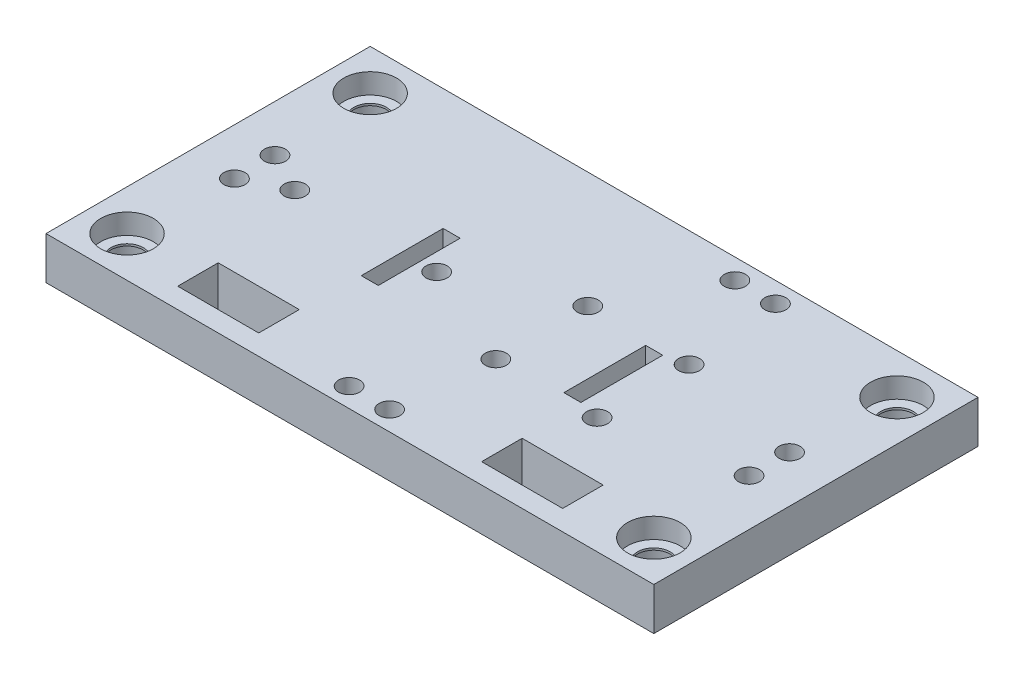
SolidWorks part; units mm, degrees
ref_plane "Front Plane" through (0, 0, 0) normal (0, 0, 1) x (1, 0, 0)
ref_plane "Top Plane" through (0, 0, 0) normal (0, 1, 0) x (1, 0, 0)
ref_plane "Right Plane" through (0, 0, 0) normal (1, 0, 0) x (0, 0, -1)
sketch "Sketch1" plane through (0, 0, 0) normal (0, 1, 0) x (1, 0, 0)
  line L1 (0, 0) -> (150, 0)
  line L2 (0, 0) -> (0, 80)
  line L3 (0, 80) -> (150, 80)
  line L4 (150, 0) -> (150, 80)
  dimension "D1" = 80
  dimension "D2" = 150
extrude "Boss-Extrude1" add sketch "Sketch1" along normal blind 10.5
sketch "Sketch10" plane through (0, 10.5, 0) normal (0, 1, 0) x (1, 0, 0)
  line L0 (75, 80) -> (75, 0) construction
  line L1 (0, 40) -> (150, 40) construction
  line L4 (0, 80) -> (0, 0)
  line L5 (0, 80) -> (0, 0) construction
  line L6 (0, 0) -> (150, 0)
  line L7 (0, 0) -> (150, 0) construction
  line L8 (150, 0) -> (150, 80)
  line L9 (150, 0) -> (150, 80) construction
  line L10 (150, 80) -> (0, 80)
  line L11 (150, 80) -> (0, 80) construction
  circle A0 centre (10, 10) radius 6.5
  circle A1 centre (140, 10) radius 6.5
  circle A3 centre (10, 70) radius 6.5
  circle A4 centre (140, 70) radius 6.5
  circle A5 centre (10, 10) radius 7.5
  circle A6 centre (10, 70) radius 7.5
  circle A7 centre (140, 70) radius 7.5
  circle A8 centre (140, 10) radius 7.5
  dimension "D4" = 13
  dimension "D2" = 10
  dimension "D3" = 10
  dimension "D1" = 0
  dimension "D5" = 1
extrude "Cut-Extrude8" cut sketch "Sketch10" against normal blind 5 contours A0 | A3 | A4 | A1 | L5 L7 L9 L11
ref_plane "MirrorPlane1" through (0, 5.25, 0) normal (0, 1, 0) x (1, 0, 0)
ref_plane "MirrorPlane2" through (0, 0, -40) normal (0, 0, 1) x (1, 0, 0)
ref_plane "MirrorPlane3" through (75, 0, 0) normal (-1, 0, 0) x (0, 0, 1)
mirror "Mirror1" about plane through (0, 5.25, 0) normal (0, 1, 0) of "Cut-Extrude8"
sketch "Sketch3" plane through (0, 10.5, 0) normal (0, 1, 0) x (1, 0, 0)
  line L0 (75, 80) -> (75, 0) construction
  line L5 (150, 80) -> (0, 80) construction
  line L6 (75, 5.775) -> (75, -5.775) construction
  line L7 (0, 0) -> (150, 0) construction
  line L8 (27.5, 15) -> (47.5, 15)
  line L9 (27.5, 15) -> (27.5, 5)
  line L10 (27.5, 5) -> (47.5, 5)
  line L11 (47.5, 15) -> (47.5, 5)
  line L12 (27.5, 15) -> (47.5, 5) construction
  line L13 (27.5, 5) -> (47.5, 15) construction
  line L15 (75, 80) -> (0, 0) construction
  line L16 (122.5, 5) -> (102.5, 5)
  line L17 (102.5, 15) -> (102.5, 5)
  line L18 (122.5, 15) -> (102.5, 15)
  line L19 (122.5, 15) -> (122.5, 5)
  point P0 (37.5, 10)
  point P16 (37.5, 40)
  dimension "D1" = 10
  dimension "D2" = 10
  dimension "D3" = 20
extrude "WireHoles" cut sketch "Sketch3" against normal up to next
sketch "Sketch6" plane through (0, 10.5, 0) normal (0, 1, 0) x (1, 0, 0)
  line L0 (75, 80) -> (75, 0) construction
  line L1 (150, 80) -> (0, 80) construction
  line L2 (0, 0) -> (150, 0) construction
  line L3 (38.9, 40) -> (21.4, 40) construction
  line L4 (73, 28.4) -> (4.8, 28.4) construction
  line L5 (73, 28.4) -> (73, 51.6) construction
  line L6 (73, 51.6) -> (4.8, 51.6) construction
  line L7 (4.8, 28.4) -> (4.8, 51.6) construction
  line L8 (73, 28.4) -> (4.8, 51.6) construction
  line L9 (73, 51.6) -> (4.8, 28.4) construction
  line L10 (38.9, 51.6) -> (38.9, 28.4) construction
  circle A0 centre (21.4, 40) radius 2.6
  circle A1 centre (56.4, 40) radius 2.6
  point P8 (38.9, 40)
  point P18 (75, 40)
  dimension "D5" = 5.2
  dimension "D1" = 68.2
  dimension "D2" = 23.2
  dimension "D3" = 2
  dimension "D4" = 17.5
extrude "4AACut" cut sketch "Sketch6" against normal blind 5.2
sketch "Sketch7" plane through (0, 10.5, 0) normal (0, 1, 0) x (1, 0, 0)
  line L0 (94.85, 51.35) -> (82.35, 51.35) construction
  line L1 (77, 42) -> (112.7, 42) construction
  line L2 (77, 42) -> (77, 60.7) construction
  line L3 (77, 60.7) -> (112.7, 60.7) construction
  line L4 (112.7, 42) -> (112.7, 60.7) construction
  line L5 (77, 42) -> (112.7, 60.7) construction
  line L6 (77, 60.7) -> (112.7, 42) construction
  line L7 (94.85, 60.7) -> (94.85, 42) construction
  line L8 (75, 80) -> (75, 0) construction
  line L9 (150, 80) -> (0, 80) construction
  line L10 (0, 0) -> (150, 0) construction
  line L11 (0, 40) -> (150, 40) construction
  line L12 (0, 80) -> (0, 0) construction
  line L13 (150, 0) -> (150, 80) construction
  circle A0 centre (82.35, 51.35) radius 2.6
  circle A1 centre (56.4, 40) radius 2.6 construction
  circle A2 centre (107.35, 51.35) radius 2.6
  circle A3 centre (82.35, 28.65) radius 2.6
  circle A4 centre (107.35, 28.65) radius 2.6
  point P0 (94.85, 51.35)
  dimension "D1" = 35.7
  dimension "D2" = 18.7
  dimension "D3" = 2
  dimension "D4" = 2
  dimension "D5" = 12.5
extrude "2AACut" cut sketch "Sketch7" against normal blind 5.2
sketch "Sketch5" plane through (0, 10.5, 0) normal (0, 1, 0) x (1, 0, 0)
  line L0 (75, 80) -> (75, 0) construction
  line L5 (150, 80) -> (0, 80) construction
  line L6 (0, 0) -> (150, 0) construction
  line L7 (50, 40) -> (75, 40) construction
  line L12 (47.9, 29.9) -> (52.1, 29.9)
  line L13 (47.9, 29.9) -> (47.9, 50.1)
  line L14 (47.9, 50.1) -> (52.1, 50.1)
  line L15 (52.1, 29.9) -> (52.1, 50.1)
  line L16 (47.9, 29.9) -> (52.1, 50.1) construction
  line L17 (47.9, 50.1) -> (52.1, 29.9) construction
  line L18 (102.1, 50.1) -> (97.9, 50.1)
  line L19 (97.9, 29.9) -> (97.9, 50.1)
  line L20 (102.1, 29.9) -> (97.9, 29.9)
  line L21 (102.1, 29.9) -> (102.1, 50.1)
  point P0 (50, 40)
  dimension "D1" = 25
  dimension "D2" = 4.2
  dimension "D3" = 20.2
extrude "ArduinoMegaCut" cut sketch "Sketch5" against normal blind 5.2
sketch "Sketch8" plane through (0, 10.5, 0) normal (0, 1, 0) x (1, 0, 0)
  line L0 (150, 80) -> (0, 80) construction
  line L5 (62.4, -2.5) -> (87.6, -2.5) construction
  line L6 (62.4, -2.5) -> (62.4, 12.1) construction
  line L7 (62.4, 12.1) -> (87.6, 12.1) construction
  line L8 (87.6, -2.5) -> (87.6, 12.1) construction
  line L9 (75, 80) -> (75, 0) construction
  line L10 (0, 0) -> (150, 0) construction
  line L11 (87.6, 4.8) -> (62.4, 4.8) construction
  circle A1 centre (70, 4.8) radius 2.6
  circle A2 centre (56.4, 40) radius 2.6 construction
  circle A3 centre (80, 4.8) radius 2.6
  point P10 (75, 12.1)
  dimension "D1" = 14.6
  dimension "D2" = 25.2
  dimension "D3" = 2.5
  dimension "D4" = 5
extrude "MPUCut" cut sketch "Sketch8" against normal blind 5.2
sketch "Sketch9" plane through (0, 10.5, 0) normal (0, 1, 0) x (1, 0, 0)
  line L0 (150, 0) -> (150, 80) construction
  line L1 (127, 51.225) -> (150, 51.225)
  line L2 (127, 51.225) -> (127, 28.775)
  line L3 (127, 28.775) -> (150, 28.775)
  line L4 (150, 51.225) -> (150, 28.775)
  line L5 (127, 51.225) -> (150, 28.775) construction
  line L6 (127, 28.775) -> (150, 51.225) construction
  line L9 (0, 40) -> (150, 40) construction
  line L10 (0, 80) -> (0, 0) construction
  line L11 (75, 80) -> (75, 0) construction
  line L12 (150, 80) -> (0, 80) construction
  line L13 (0, 0) -> (150, 0) construction
  circle A0 centre (138.5, 45) radius 2.6
  circle A1 centre (107.35, 51.35) radius 2.6 construction
  circle A2 centre (138.5, 35) radius 2.6
  circle A3 centre (11.5, 35) radius 2.6
  circle A4 centre (11.5, 45) radius 2.6
  point P0 (138.5, 40)
  dimension "D1" = 22.45
  dimension "D2" = 23
  dimension "D3" = 5
extrude "Cut-Extrude7" cut sketch "Sketch9" against normal up to next contours A0 | A2 | A4 | A3
sketch "Sketch11" plane through (0, 5.5, 0) normal (0, 1, 0) x (1, 0, 0)
  line L0 (0, 40) -> (150, 40) construction
  line L1 (0, 80) -> (0, 0) construction
  line L2 (150, 0) -> (150, 80) construction
  line L3 (75, 80) -> (75, 0) construction
  line L4 (150, 80) -> (0, 80) construction
  line L5 (0, 0) -> (150, 0) construction
  circle A0 centre (10, 10) radius 4
  circle A1 centre (10, 70) radius 4
  circle A2 centre (140, 70) radius 4
  circle A3 centre (140, 10) radius 4
  dimension "D1" = 8
extrude "Cut-Extrude9" cut sketch "Sketch11" against normal up to surface (0.5 mm away) up to face at (10, 5, -63.5)
sketch "Sketch12" plane through (0, 10.5, 0) normal (0, 1, 0) x (1, 0, 0)
  line L0 (100, 80) -> (100, 0) construction
  line L1 (150, 80) -> (0, 80) construction
  line L2 (0, 0) -> (150, 0) construction
  line L3 (150, 0) -> (150, 80) construction
  circle A0 centre (95, 75) radius 2.6
  circle A1 centre (82.35, 51.35) radius 2.6 construction
  circle A4 centre (105, 75) radius 2.6
  dimension "D1" = 50
  dimension "D2" = 10
  dimension "D3" = 5
extrude "Cut-Extrude10" cut sketch "Sketch12" against normal blind 5
equation "\"Depth\"= 5.20"
